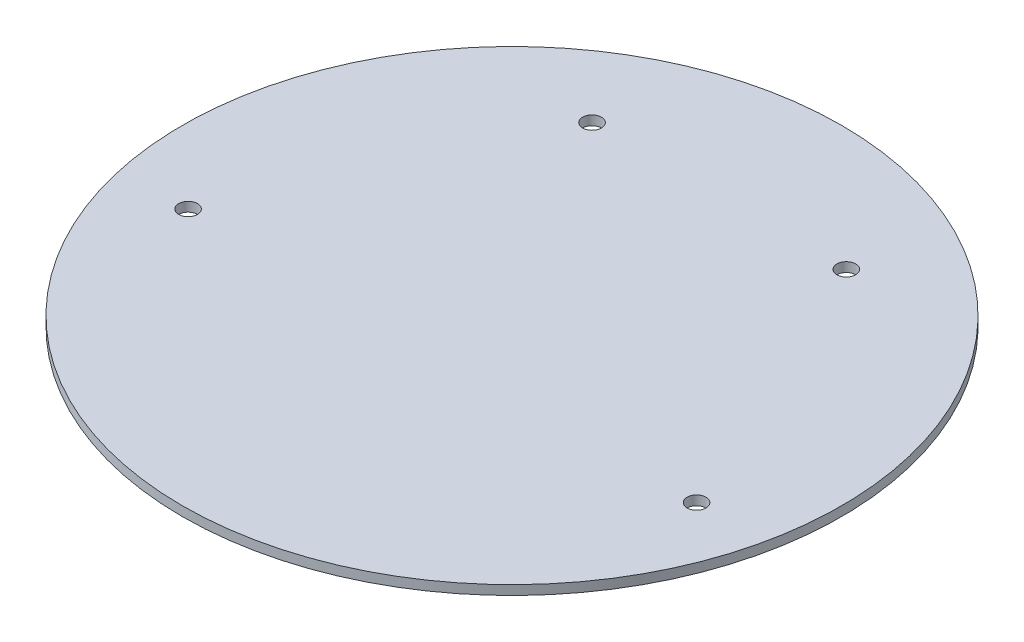
SolidWorks part; units mm, degrees
ref_plane "Front Plane" through (0, 0, 0) normal (0, 0, 1) x (1, 0, 0)
ref_plane "Top Plane" through (0, 0, 0) normal (0, 1, 0) x (1, 0, 0)
ref_plane "Right Plane" through (0, 0, 0) normal (1, 0, 0) x (0, 0, -1)
sketch "Sketch1" plane through (0, 0, 0) normal (0, 1, 0) x (1, 0, 0)
  line L0 (-27, -7.4) -> (27, -7.4) construction
  line L1 (-13.5, 22) -> (13.5, 22) construction
  circle A0 centre (0, 0) radius 35
  circle A1 centre (-27, -7.4) radius 1
  circle A2 centre (27, -7.4) radius 1
  circle A3 centre (-13.5, 22) radius 1
  circle A4 centre (13.5, 22) radius 1
  point P7 (0, -7.4)
  point P12 (0, 22)
  point P13 (6.931, 22)
  dimension "D1" = 70
  dimension "D2" = 2
  dimension "D3" = 7.4
  dimension "D4" = 54
  dimension "D5" = 22
  dimension "D6" = 27
extrude "Boss-Extrude1" add sketch "Sketch1" along normal mid plane 1
